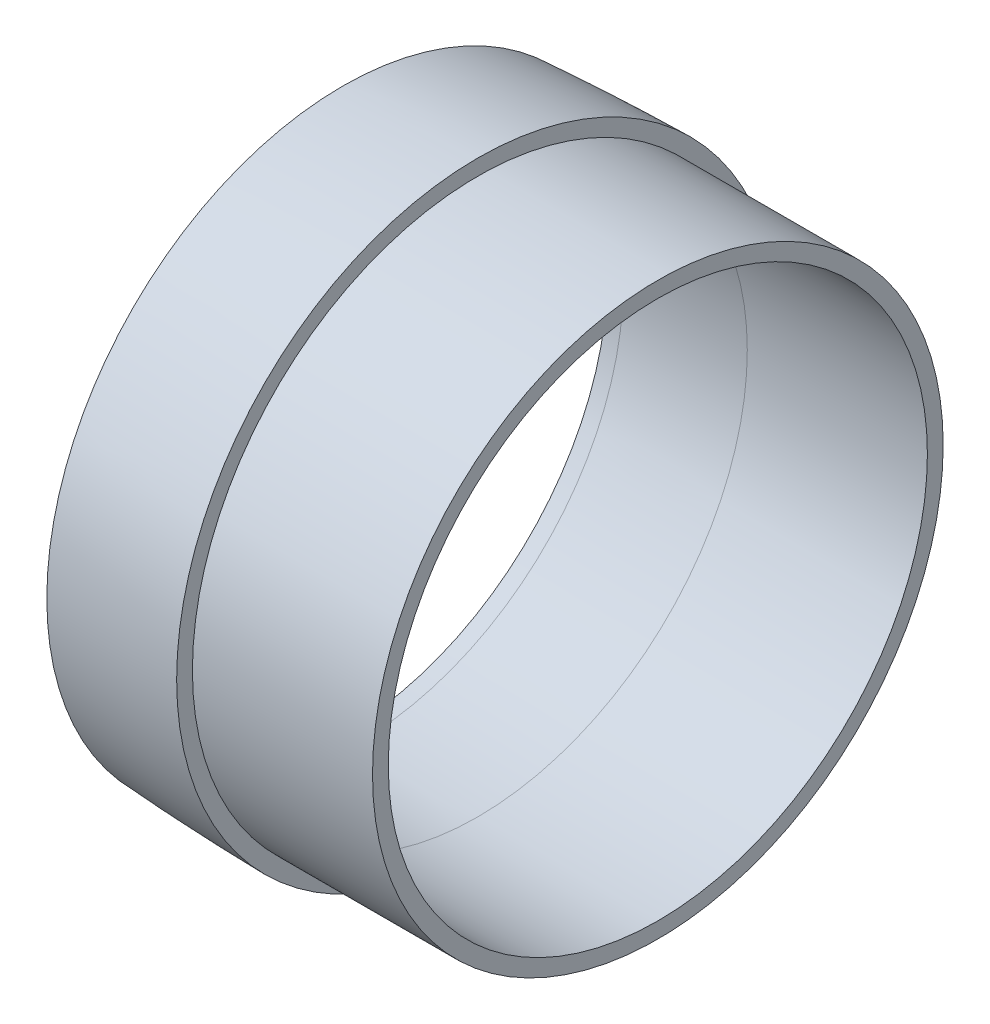
SolidWorks part; units mm, degrees
ref_plane "Front Plane" through (0, 0, 0) normal (0, 0, 1) x (1, 0, 0)
ref_plane "Top Plane" through (0, 0, 0) normal (0, 1, 0) x (1, 0, 0)
ref_plane "Right Plane" through (0, 0, 0) normal (1, 0, 0) x (0, 0, -1)
sketch "Sketch1" plane through (0, 0, 0) normal (0, 0, 1) x (1, 0, 0)
  line L4 (200, 33.4356) -> (200, 0)
  line L5 (200, 0) -> (0, 0)
  spline S0 degree 4 poles (0, 0) (0.0297, 0.0027) (0.089, 0.0128) (0.1752, 0.0408) (0.3046, 0.0915) (0.5495, 0.204) (0.9043, 0.3864) (1.5855, 0.7376) (2.7098, 1.2836) (4.4238, 2.0401) (7.065, 3.0857) (10.7984, 4.4109) (16.1615, 6.1222) (23.7399, 8.2919) (33.2254, 10.7239) (44.2444, 13.2746) (56.1293, 15.7818) (68.0528, 18.0982) (80.0071, 20.2486) (91.9875, 22.2489) (103.9905, 24.1086) (116.0136, 25.8328) (128.0552, 27.4233) (140.114, 28.8776) (152.1891, 30.1899) (164.2801, 31.3479) (176.3866, 32.3324) (186.1546, 32.954) (193.5759, 33.2951) (197.9667, 33.411) (199.3222, 33.4323) (200, 33.4356) knots 0 0 0 0 0 0.000585 0.001182 0.001773 0.002733 0.005878 0.009023 0.016834 0.027293 0.042687 0.064838 0.094675 0.13791 0.197585 0.25726 0.316935 0.37661 0.436285 0.495959 0.555634 0.615309 0.674984 0.734659 0.794334 0.854008 0.913683 0.973358 0.986679 1 1 1 1 1 construction
  spline S1 degree 4 poles (0, 0) (0.0297, 0.0027) (0.089, 0.0128) (0.1752, 0.0408) (0.3046, 0.0915) (0.5495, 0.204) (0.9043, 0.3864) (1.5855, 0.7376) (2.7098, 1.2836) (4.4238, 2.0401) (7.065, 3.0857) (10.7984, 4.4109) (16.1615, 6.1222) (23.7399, 8.2919) (33.2254, 10.7239) (44.2444, 13.2746) (56.1293, 15.7818) (68.0528, 18.0982) (80.0071, 20.2486) (91.9875, 22.2489) (103.9905, 24.1086) (116.0136, 25.8328) (128.0552, 27.4233) (140.114, 28.8776) (152.1891, 30.1899) (164.2801, 31.3479) (176.3866, 32.3324) (186.1546, 32.954) (193.5759, 33.2951) (197.9667, 33.411) (199.3222, 33.4323) (200, 33.4356) knots 0 0 0 0 0 0.000585 0.001182 0.001773 0.002733 0.005878 0.009023 0.016834 0.027293 0.042687 0.064838 0.094675 0.13791 0.197585 0.25726 0.316935 0.37661 0.436285 0.495959 0.555634 0.615309 0.674984 0.734659 0.794334 0.854008 0.913683 0.973358 0.986679 1 1 1 1 1
  dimension "D1" = 200
revolve "Revolve1" add sketch "Sketch1" angle 360 about L5
shell "Shell2" thickness 1.75
ref_plane "Plane1" through (185, 0, 0) normal (1, 0, 0) x (0, 0, -1)
sketch "Sketch3" plane through (185, 0, 0) normal (1, 0, 0) x (0, 0, -1)
  circle A0 centre (0, 0) radius 33.4356
  circle A1 centre (0, 0) radius 33.4356 construction
extrude "Cut-Extrude1" cut sketch "Sketch3" against normal through all contours A0
sketch "Sketch4" plane through (185, 0, 0) normal (-1, 0, 0) x (0, 0, 1)
  circle A0 centre (0, 0) radius 31.0982
  circle A1 centre (0, 0) radius 31.0982 construction
sketch "Sketch5" plane through (200, 0, 0) normal (1, 0, 0) x (0, 0, -1)
  circle A0 centre (0, 0) radius 31.6855
  circle A1 centre (0, 0) radius 31.6855 construction
loft "Loft2" add profiles "Sketch5", "Sketch4"
shell "Shell3" thickness 1.75
sketch "Sketch6" plane through (186.75, 0, 0) normal (1, 0, 0) x (0, 0, -1)
  circle A0 centre (0, 0) radius 29.4154
  circle A1 centre (0, 0) radius 29.4154 construction
extrude "Cut-Extrude2" cut sketch "Sketch6" against normal blind 10
sketch "Sketch7" plane through (200, 0, 0) normal (1, 0, 0) x (0, 0, -1)
  circle A0 centre (0, 0) radius 31.6855
  circle A1 centre (0, 0) radius 29.9342
  circle A2 centre (0, 0) radius 31.6855 construction
  circle A3 centre (0, 0) radius 29.9342 construction
extrude "Boss-Extrude1" add sketch "Sketch7" along normal blind 20
